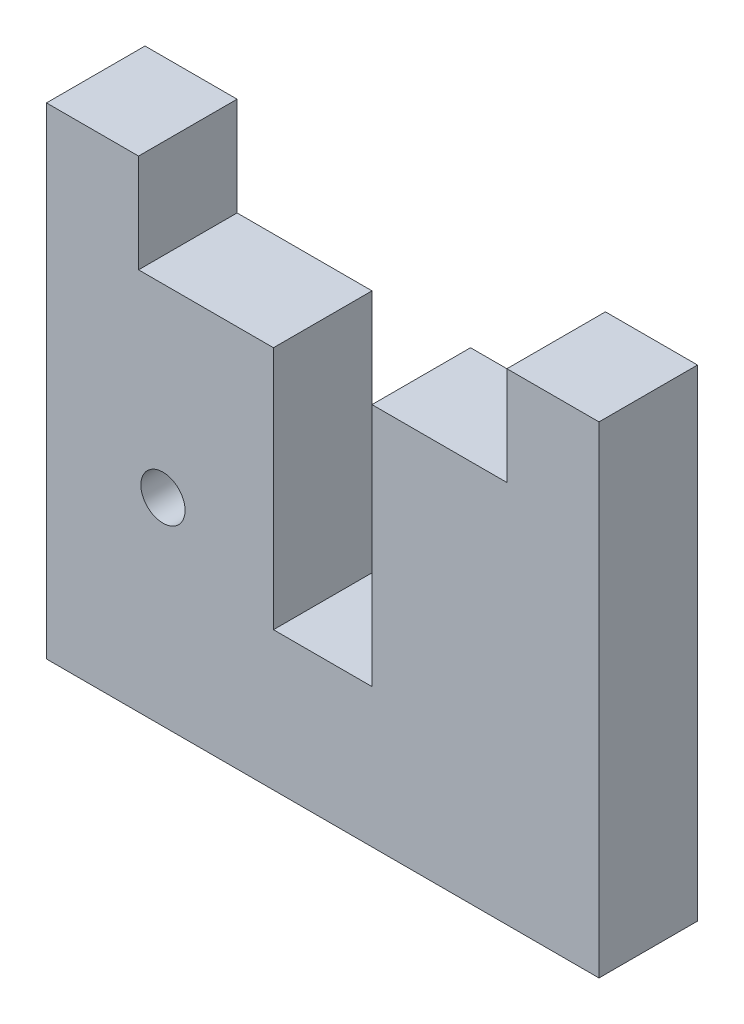
SolidWorks part; units mm, degrees
ref_plane "Front Plane" through (0, 0, 0) normal (0, 0, 1) x (1, 0, 0)
ref_plane "Top Plane" through (0, 0, 0) normal (0, 1, 0) x (1, 0, 0)
ref_plane "Right Plane" through (0, 0, 0) normal (1, 0, 0) x (0, 0, -1)
sketch "Model" plane through (0, 0, 0) normal (0, 0, 1) x (1, 0, 0)
  line L0 (10, 26.15) -> (15, 26.15)
  line L1 (-15, 0) -> (15, 0)
  line L2 (-15, 0) -> (-15, 26.15)
  line L3 (-15, 26.15) -> (-10, 26.15)
  line L4 (15, 0) -> (15, 26.15)
  line L5 (2.675, 20.8) -> (10, 20.8)
  line L6 (-10, 26.15) -> (-10, 20.8)
  line L7 (-10, 20.8) -> (-2.675, 20.8)
  line L8 (10, 26.15) -> (10, 20.8)
  line L10 (-2.675, 20.8) -> (-2.675, 7.5398)
  line L11 (-2.675, 7.5398) -> (2.675, 7.5398)
  line L12 (2.675, 20.8) -> (2.675, 7.5398)
  circle A0 centre (-8.675, 10.75) radius 1.2
  dimension "D15" = 2.4
  dimension "D2" = 30
  dimension "D6" = 5
  dimension "D7" = 26.15
  dimension "D10" = 5.35
  dimension "D11" = 5.35
  dimension "D13" = 7.5398
  dimension "D17" = 6.325
  dimension "D19" = 10.75
extrude "Boss-Extrude1" add sketch "Model" along normal blind 5.35
equation "\"mdfthick\"=5.35"
equation "\"D10@Model\"=\"mdfthick\""
equation "\"D11@Model\"=\"mdfthick\""
equation "\"D1@Boss-Extrude1\"=\"mdfthick\""
